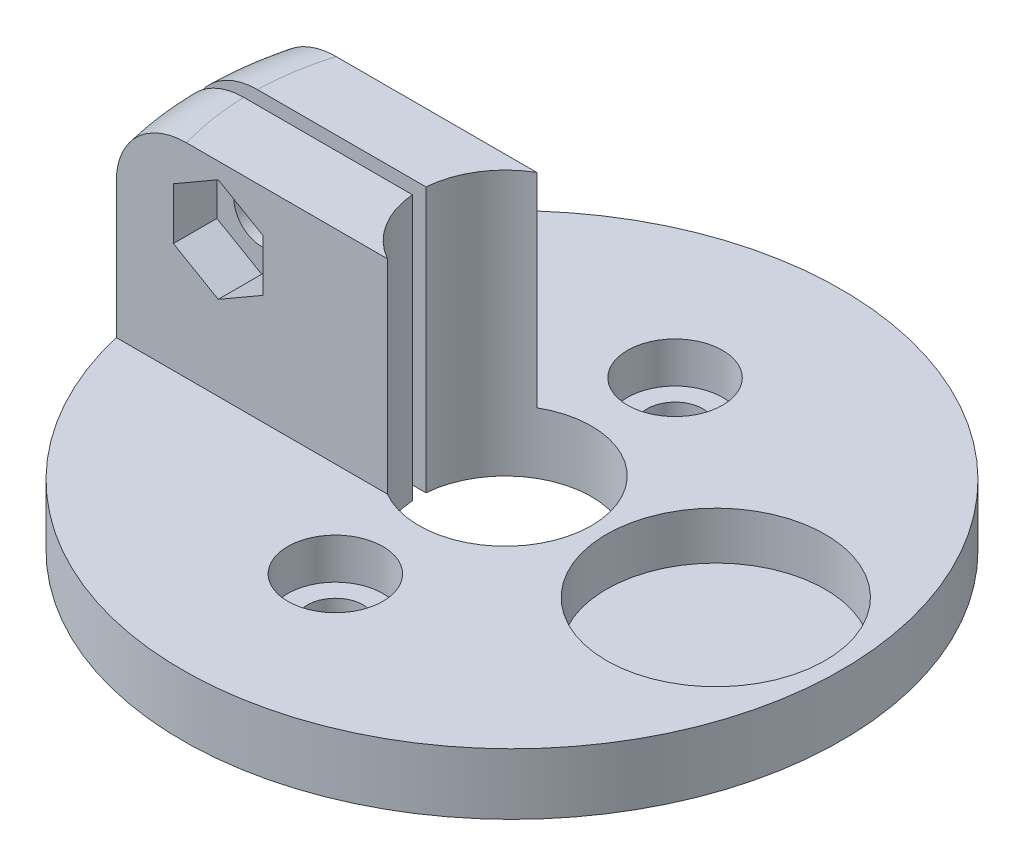
SolidWorks part; units mm, degrees
ref_plane "Front Plane" through (0, 0, 0) normal (0, 0, 1) x (1, 0, 0)
ref_plane "Top Plane" through (0, 0, 0) normal (0, 1, 0) x (1, 0, 0)
ref_plane "Right Plane" through (0, 0, 0) normal (1, 0, 0) x (0, 0, -1)
sketch "Sketch2" plane through (0, 0, 0) normal (0, 1, 0) x (1, 0, 0)
  line L0 (1, 0) -> (-47.5, 0) construction
  line L1 (-12.6606, 1) -> (-47.5, 1)
  line L2 (-12.6606, -1) -> (-47.5, -1)
  line L3 (1, 1) -> (-47.5, 1) construction
  line L4 (1, -1) -> (-47.5, -1) construction
  circle A0 centre (1, 0) radius 48.5
  circle A2 centre (0, 0) radius 12.7
  dimension "D1" = 97
  dimension "D2" = 25.4
  dimension "D3" = 1
  dimension "D4" = 1
extrude "Boss-Extrude2" add sketch "Sketch2" along normal blind 9 contours A2 L2 A0 L1
sketch "Sketch4" plane through (0, 9, 0) normal (0, 1, 0) x (1, 0, 0)
  circle A2 centre (31, 0) radius 16.1
  dimension "D1" = 31
  dimension "D5" = 32.2
extrude "Cut-Extrude1" cut sketch "Sketch4" against normal blind 7
sketch "Sketch5" plane through (0, 9, 0) normal (0, 1, 0) x (1, 0, 0)
  line L0 (0, 25) -> (0, -25) construction
  point P5 (0, 0)
  point P7 (0, -25)
  point P8 (0, 25)
  dimension "D1" = 25
hole_wizard "CBORE for M8 Hex Head Bolt1" positions "3DSketch1" profile "Sketch6" counterbore size "M8" standard "DIN"
sketch3d "3DSketch1"
  point P0 (0, 9, 25)
  point P3 (0, 9, -25)
sketch "Sketch6" plane through (0, 9, 25) normal (1, 0, 0) x (0, 0, 1)
  line L0 (0, 0) -> (0, 12.4635)
  line L1 (0, 12.4635) -> (4.1, 10)
  line L2 (4.1, 10) -> (4.1, 6)
  line L3 (4.1, 6) -> (7, 6)
  line L4 (7, 6) -> (7, 0)
  line L5 (7, 0) -> (0, 0)
  line L10 (0, 12.4635) -> (-4.1, 10) construction
  line L11 (0, -6.35) -> (0, 107.95) construction
  dimension "Hole Dia." = 8.2
  dimension "Hole Depth" = 10
  dimension "C'Bore Dia." = 14
  dimension "C'Bore Depth" = 6
  dimension "Drill Angle" = 118
sketch "Sketch7" plane through (0, 9, 0) normal (0, 1, 0) x (1, 0, 0)
  line L0 (-12.6606, 1) -> (-47.4897, 1) construction
  line L1 (-12.6606, -1) -> (-47.4897, -1) construction
  line L2 (-12.6606, 1) -> (-47.4897, 1)
  line L3 (-12.6606, -1) -> (-47.4897, -1)
  line L4 (-46.2361, -11) -> (-6.3474, -11)
  line L5 (-6.3474, 11) -> (-46.2361, 11)
  arc A0 (-47.4897, -1) -> (-47.4897, 1) centre (1, 0) ccw construction
  arc A1 (-12.6606, -1) -> (-12.6606, 1) centre (0, 0) ccw construction
  arc A2 (-47.4897, -1) -> (-47.4897, 1) centre (1, 0) ccw
  arc A3 (-12.6606, -1) -> (-12.6606, 1) centre (0, 0) ccw
  arc M9 (-12.6606, 1) -> (-12.6606, -1) centre (0, 0) cw
  line M10 (-12.6606, -1) -> (-47.4897, -1)
  arc M11 (-47.4897, -1) -> (-47.4897, 1) centre (1, 0) ccw
  line M12 (-47.4897, 1) -> (-12.6606, 1)
  dimension "D1" = 10
  dimension "D2" = 10
extrude "Boss-Extrude3" add sketch "Sketch7" along normal blind 30 contours L4 M11 M9 M10 | L5 M9 M11 M12
sketch "Sketch8" plane through (0, 0, -11) normal (0, 0, -1) x (-1, 0, 0)
  line L0 (6.3474, 39) -> (46.2361, 39) construction
  line L1 (46.2361, 39) -> (46.2361, 9) construction
  circle A0 centre (31.2361, 29) radius 4.1
  dimension "D1" = 8.2
  dimension "D2" = 10
  dimension "D3" = 15
extrude "Cut-Extrude2" cut sketch "Sketch8" against normal through all
sketch "Sketch9" plane through (0, 0, 11) normal (0, 0, 1) x (1, 0, 0)
  line L1 (-24.6361, 25.1895) -> (-24.6361, 32.8105)
  line L2 (-24.6361, 32.8105) -> (-31.2361, 36.621)
  line L3 (-31.2361, 36.621) -> (-37.8361, 32.8105)
  line L4 (-37.8361, 32.8105) -> (-37.8361, 25.1895)
  line L5 (-37.8361, 25.1895) -> (-31.2361, 21.379)
  line L6 (-31.2361, 21.379) -> (-24.6361, 25.1895)
  circle A0 centre (-31.2361, 29) radius 6.6 construction
  dimension "D1" = 13.2
extrude "Cut-Extrude3" cut sketch "Sketch9" against normal blind 6.4
fillet "Fillet1" radius 10 2 edges at (-47.1234, 39, -6.0327) (-47.1234, 39, 6.0327)
